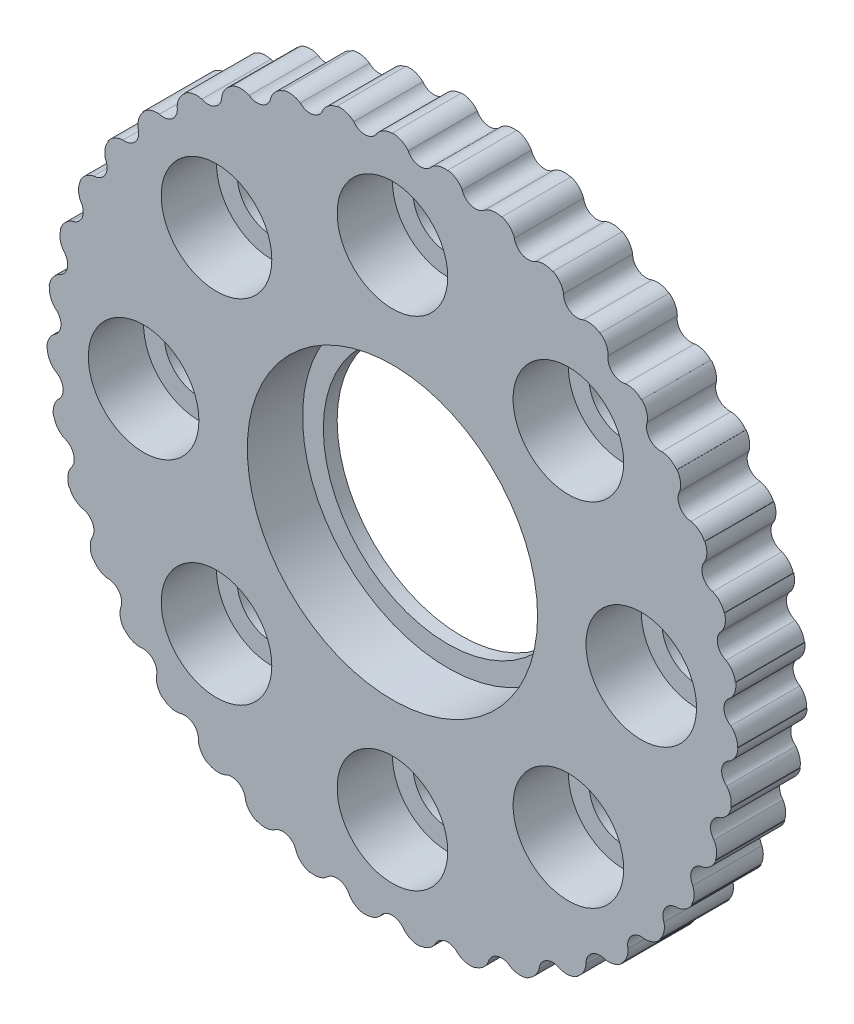
SolidWorks part; units mm, degrees
ref_plane "Plan de face" through (0, 0, 0) normal (0, 0, 1) x (1, 0, 0)
ref_plane "Plan de dessus" through (0, 0, 0) normal (0, 1, 0) x (1, 0, 0)
ref_plane "Plan de droite" through (0, 0, 0) normal (1, 0, 0) x (0, 0, -1)
sketch "Esquisse1" plane through (0, 0, 0) normal (0, 0, 1) x (1, 0, 0)
  line L0 (0, 18) -> (0, 27.9712) construction
  line L1 (0, 25.02) -> (0, 0)
  line L2 (0, 0) -> (5.0142, 23.9582)
  arc A7 (0, 25.02) -> (1.1384, 24.468) centre (0, 23.57) cw
  arc A8 (1.1384, 24.468) -> (2.824, 24.3069) centre (2.0318, 24.9173) ccw
  arc A9 (2.824, 24.3069) -> (5.0142, 23.9582) centre (3.7809, 23.2648) cw
  point P128 (0, 0)
  dimension "D2" = 23.57
  dimension "D7" = 1
  dimension "D10" = 1.45
  dimension "D3" = 25
  dimension "D8" = 3.7809
extrude "Boss.-Extru.1" add sketch "Esquisse1" along normal blind 5
pattern_circular "Répétition circulaire1" count 39 every 9.231 about axis through (0, 0, 0) along (0, 0, 1) of "Boss.-Extru.1"
sketch "Esquisse2" plane through (0, 0, 5) normal (0, 0, 1) x (1, 0, 0)
  line L0 (0, 0) -> (0, 18) construction
  line L1 (0, 0) -> (0, 33.0867) construction
  circle A0 centre (0, 18) radius 4
  circle A1 centre (0, 0) radius 9.5
  circle A9 centre (12.7279, 12.7279) radius 4
  circle A10 centre (18, 0) radius 4
  circle A11 centre (12.7279, -12.7279) radius 4
  circle A12 centre (0, -18) radius 4
  circle A13 centre (-12.7279, -12.7279) radius 4
  circle A14 centre (-18, 0) radius 4
  circle A15 centre (-12.7279, 12.7279) radius 4
  point P21 (0, 0)
  point P23 (0, 0)
  dimension "D2" = 8
  dimension "D3" = 19
  dimension "D1" = 18
  dimension "D5" = 8
extrude "Enlèv. mat.-Extru.1" cut sketch "Esquisse2" against normal blind 4
sketch "Esquisse5" plane through (0, 0, 5) normal (0, 0, 1) x (1, 0, 0)
  circle A0 centre (0, 0) radius 10.5
  dimension "D1" = 21
extrude "Enlèv. mat.-Extru.2" cut sketch "Esquisse5" against normal blind 4
sketch "Esquisse6" plane through (0, 0, 1) normal (0, 0, 1) x (1, 0, 0)
  circle A0 centre (0, 18) radius 2.5
  circle A1 centre (0, 18) radius 4 construction
  circle A2 centre (0, 0) radius 9
  circle A3 centre (12.7279, 12.7279) radius 2.5
  circle A4 centre (18, 0) radius 2.5
  circle A5 centre (12.7279, -12.7279) radius 2.5
  circle A6 centre (0, -18) radius 2.5
  circle A7 centre (-12.7279, -12.7279) radius 2.5
  circle A8 centre (-18, 0) radius 2.5
  circle A9 centre (-12.7279, 12.7279) radius 2.5
  point P23 (0, 0)
  dimension "D1" = 5
  dimension "D2" = 18
  dimension "D3" = 8
extrude "Enlèv. mat.-Extru.3" cut sketch "Esquisse6" against normal through all
